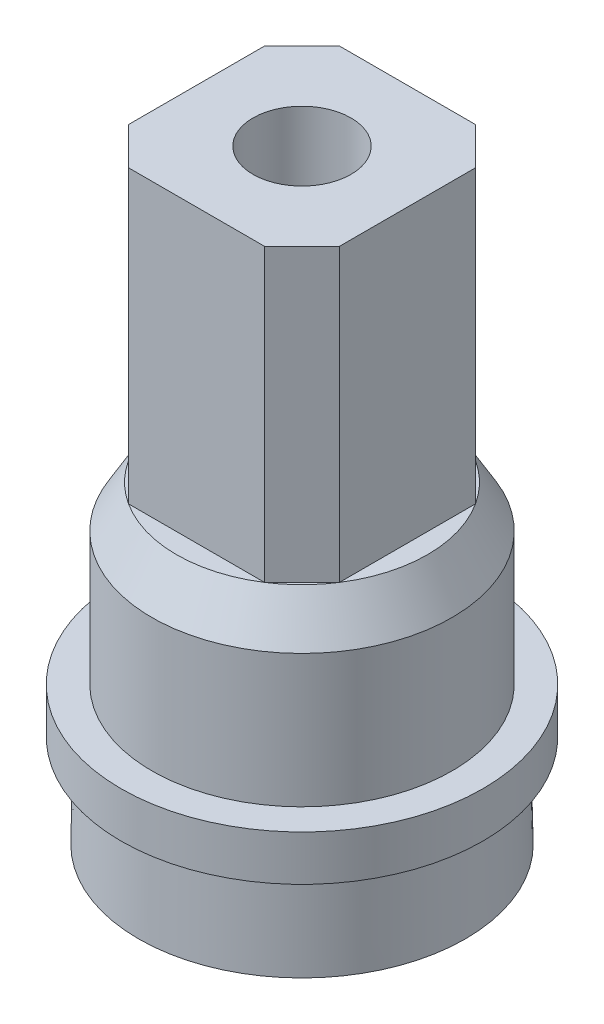
SolidWorks part; units mm, degrees
ref_plane "Front Plane" through (0, 0, 0) normal (0, 0, 1) x (1, 0, 0)
ref_plane "Top Plane" through (0, 0, 0) normal (0, 1, 0) x (1, 0, 0)
ref_plane "Right Plane" through (0, 0, 0) normal (1, 0, 0) x (0, 0, -1)
sketch "Sketch1" plane through (0, 0, 0) normal (0, 0, 1) x (1, 0, 0)
  line L0 (0, 0) -> (0, 12.6983) construction
  line L1 (-2.7, 0) -> (-2.7, 5.54)
  line L2 (-2.7, 5.54) -> (-1.295, 5.54)
  line L3 (-1.295, 5.54) -> (-1.295, 8.3)
  line L4 (-1.295, 8.3) -> (-3.32, 8.3)
  line L5 (-3.32, 8.3) -> (-3.97, 7.1844)
  line L6 (-3.97, 7.1844) -> (-3.97, 3.67)
  line L7 (-3.97, 3.67) -> (-4.785, 3.67)
  line L8 (-4.785, 3.67) -> (-4.785, 2.47)
  line L9 (-4.785, 2.47) -> (-4.28, 2.47)
  line L10 (-4.28, 2.47) -> (-4.325, 0)
  line L11 (-4.325, 0) -> (-2.7, 0)
  dimension "D1" = 9.57
  dimension "D2" = 8.3
  dimension "D3" = 3.67
  dimension "D4" = 1.2
  dimension "D5" = 8.65
  dimension "D6" = 8.56
  dimension "D7" = 5.4
  dimension "D8" = 6.64
  dimension "D9" = 7.94
  dimension "D10" = 1.1156
  dimension "D11" = 2.59
  dimension "D12" = 5.54
revolve "Revolve1" add sketch "Sketch1" angle 360 about L0
sketch "Sketch2" plane through (0, 8.3, 0) normal (0, 1, 0) x (1, 0, 0)
  line L0 (1.7995, 2.79) -> (-1.7995, 2.79)
  line L1 (-1.7995, 2.79) -> (-2.79, 1.7995)
  line L2 (-2.79, 1.7995) -> (-2.79, -1.7995)
  line L3 (-2.79, -1.7995) -> (-1.7995, -2.79)
  line L4 (-1.7995, -2.79) -> (1.7995, -2.79)
  line L5 (1.7995, -2.79) -> (2.79, -1.7995)
  line L6 (2.79, -1.7995) -> (2.79, 1.7995)
  line L7 (2.79, 1.7995) -> (1.7995, 2.79)
  circle A0 centre (0, 0) radius 3.32 construction
  circle A1 centre (0, 0) radius 1.295
  dimension "D1" = 5.58
  dimension "D2" = 1.4007
extrude "Boss-Extrude1" add sketch "Sketch2" along normal blind 7.7
